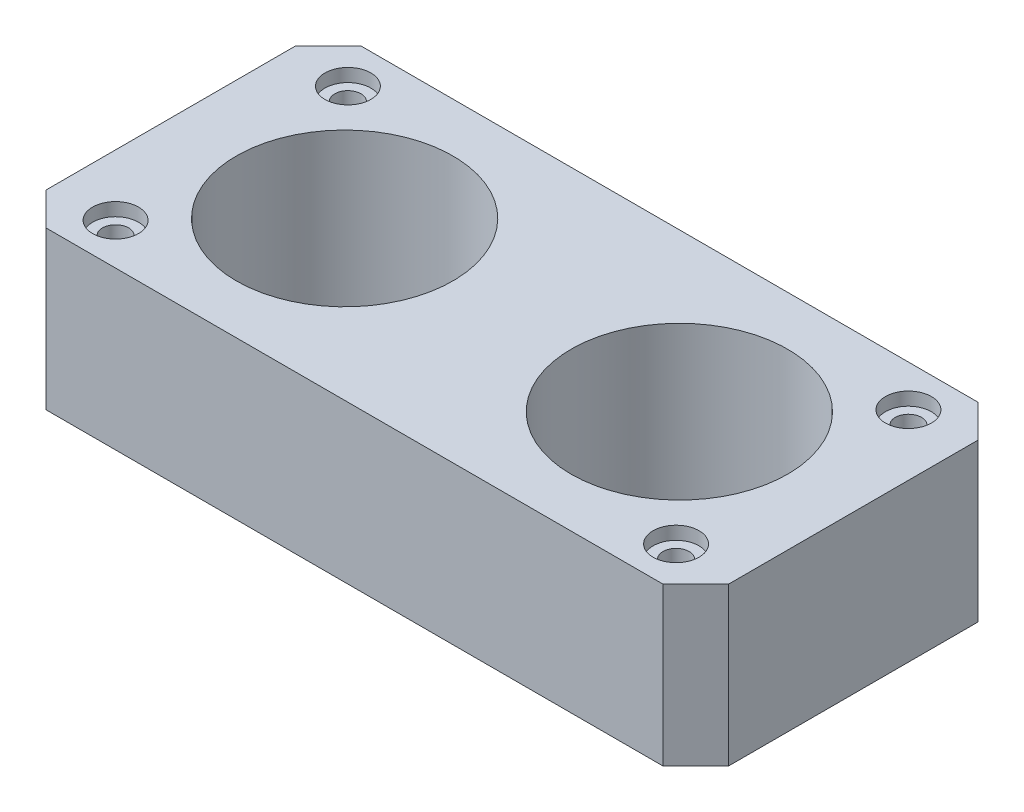
SolidWorks part; units mm, degrees
ref_plane "Front Plane" through (0, 0, 0) normal (0, 0, 1) x (1, 0, 0)
ref_plane "Top Plane" through (0, 0, 0) normal (0, 1, 0) x (1, 0, 0)
ref_plane "Right Plane" through (0, 0, 0) normal (1, 0, 0) x (0, 0, -1)
sketch "Sketch1" plane through (0, 0, 0) normal (0, 1, 0) x (1, 0, 0)
  line L0 (-12.75, 0) -> (12.75, 0) construction
  line L1 (-26, 12) -> (26, 12)
  line L2 (-26, 12) -> (-26, -12)
  line L3 (-26, -12) -> (26, -12)
  line L4 (26, 12) -> (26, -12)
  line L5 (-26, 12) -> (26, -12) construction
  line L6 (-26, -12) -> (26, 12) construction
  circle A0 centre (12.75, 0) radius 8.25
  circle A1 centre (-12.75, 0) radius 8.25
  point P0 (0, 0)
  point P9 (0, 0)
  dimension "D3" = 16.5
  dimension "D1" = 52
  dimension "D2" = 24
  dimension "D4" = 25.5
extrude "Boss-Extrude1" add sketch "Sketch1" along normal blind 12
sketch "Sketch2" plane through (0, 12, 0) normal (0, 1, 0) x (1, 0, 0)
  line L1 (-21.35, 8.85) -> (21.35, 8.85) construction
  line L2 (-21.35, 8.85) -> (-21.35, -8.85) construction
  line L3 (-21.35, -8.85) -> (21.35, -8.85) construction
  line L4 (21.35, 8.85) -> (21.35, -8.85) construction
  line L5 (-21.35, 8.85) -> (21.35, -8.85) construction
  line L6 (-21.35, -8.85) -> (21.35, 8.85) construction
  circle A0 centre (-21.35, 8.85) radius 1
  circle A1 centre (21.35, 8.85) radius 1
  circle A2 centre (21.35, -8.85) radius 1
  circle A3 centre (-21.35, -8.85) radius 1
  point P0 (0, 0)
  dimension "D3" = 2
  dimension "D1" = 17.7
  dimension "D2" = 42.7
extrude "Cut-Extrude1" cut sketch "Sketch2" against normal through all
sketch "Sketch3" plane through (0, 12, 0) normal (0, 1, 0) x (1, 0, 0)
  circle A20 centre (-21.35, 8.85) radius 1.75
  circle A21 centre (21.35, 8.85) radius 1.75
  circle A23 centre (21.35, -8.85) radius 1.75
  circle A24 centre (-21.35, -8.85) radius 1.75
  dimension "D1" = 3.5
extrude "Cut-Extrude2" cut sketch "Sketch3" against normal blind 1
sketch "Sketch4" plane through (0, 0, 0) normal (0, -1, 0) x (1, 0, 0)
  line L0 (26, -12) -> (-26, -12) construction
  line L1 (-6, -12) -> (6, -12)
  line L2 (-6, -12) -> (-6, -5)
  line L3 (-6, -5) -> (6, -5)
  line L4 (6, -12) -> (6, -5)
  line L5 (0, -5) -> (0, 0)
  line M14 (-26, -12) -> (26, -12)
  dimension "D1" = 7
  dimension "D2" = 12
extrude "Cut-Extrude3" cut sketch "Sketch4" against normal blind 5 contours L4 L3 L2 M14
fillet "Fillet3" radius 0.5 5 edges at (-6, 5, -8.5) (6, 5, -8.5) (6, 2.5, -5) (0, 5, -5) (-6, 2.5, -5)
chamfer "Chamfer1" distance 2.5 4 edges at (26, 6, 12) (26, 6, -12) (-26, 6, -12) (-26, 6, 12)
